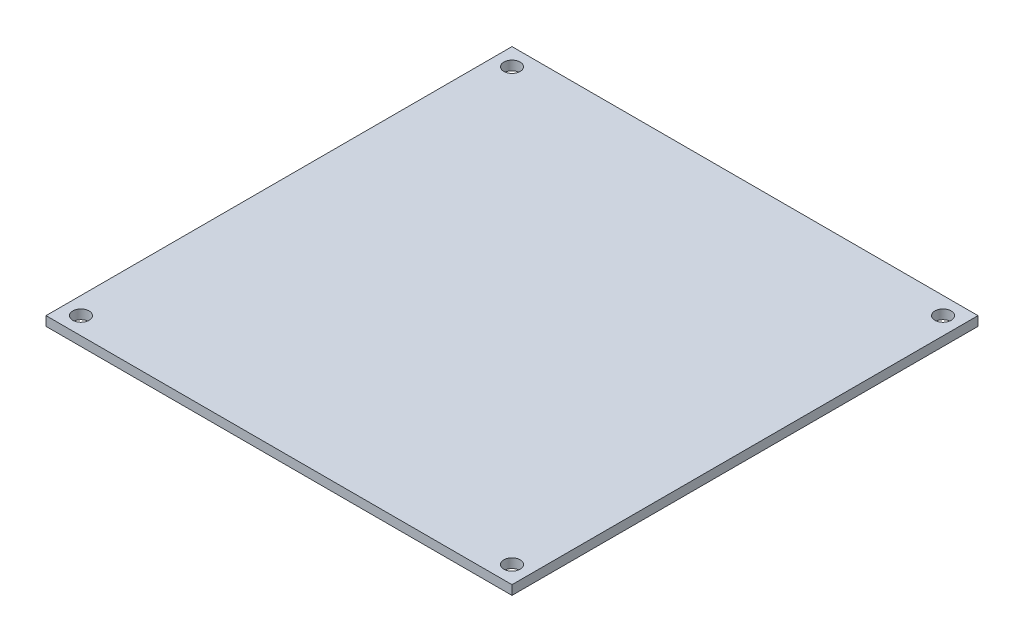
SolidWorks part; units mm, degrees
ref_plane "정면" through (0, 0, 0) normal (0, 0, 1) x (1, 0, 0)
ref_plane "윗면" through (0, 0, 0) normal (0, 1, 0) x (1, 0, 0)
ref_plane "우측면" through (0, 0, 0) normal (1, 0, 0) x (0, 0, -1)
sketch "스케치2" plane through (0, 0, 0) normal (0, 1, 0) x (1, 0, 0)
  line L0 (0, 50) -> (0, -50) construction
  line L5 (50, -50) -> (-50, -50)
  line L6 (50, -50) -> (50, 50)
  line L7 (50, 50) -> (-50, 50)
  line L8 (-50, -50) -> (-50, 50)
  line L9 (50, -50) -> (-50, 50) construction
  line L10 (50, 50) -> (-50, -50) construction
  line L11 (-50, 0) -> (50, 0) construction
  circle A0 centre (-46.25, 46.25) radius 1.75
  circle A1 centre (46.25, 46.25) radius 1.75
  circle A2 centre (46.25, -46.25) radius 1.75
  circle A3 centre (-46.25, -46.25) radius 1.75
  point P0 (0, 0)
  dimension "D3" = 3.5
  dimension "D1" = 100
  dimension "D2" = 100
  dimension "D4" = 3.75
  dimension "D5" = 3.75
extrude "보스-돌출1" add sketch "스케치2" along normal blind 2
